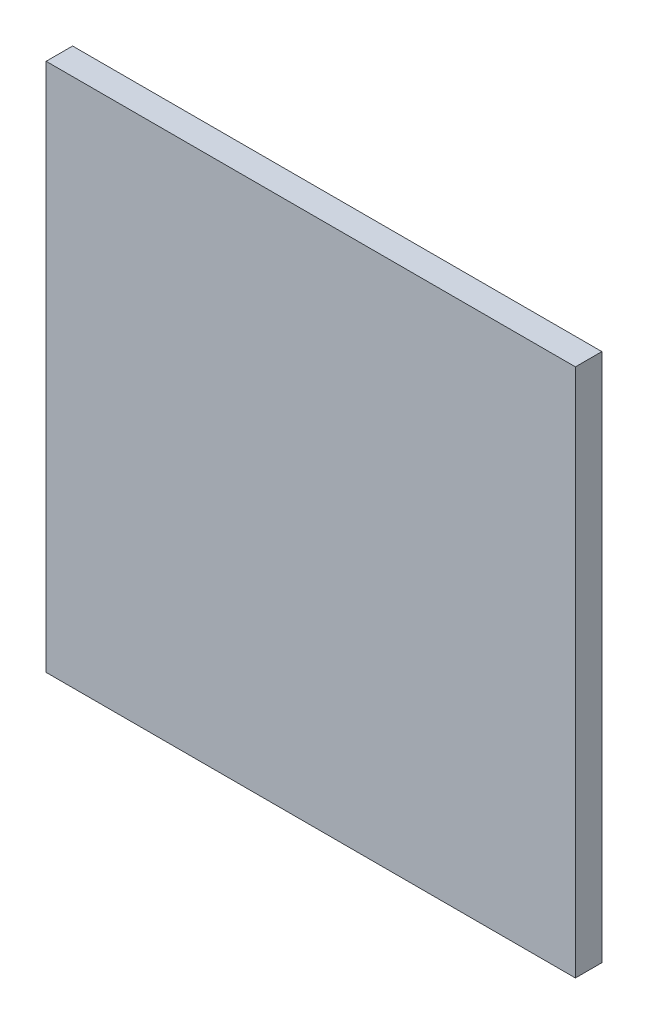
SolidWorks part; units mm, degrees
ref_plane "Front" through (0, 0, 0) normal (0, 0, 1) x (1, 0, 0)
ref_plane "Top" through (0, 0, 0) normal (0, 1, 0) x (1, 0, 0)
ref_plane "Right" through (0, 0, 0) normal (1, 0, 0) x (0, 0, -1)
other "Configuration Table"
sketch "Sketch1" plane through (0, 0, 0) normal (0, 0, 1) x (1, 0, 0)
  line L1 (-10, -10) -> (10, -10)
  line L2 (-10, -10) -> (-10, 10)
  line L3 (-10, 10) -> (10, 10)
  line L4 (10, -10) -> (10, 10)
  point P4 (0, -10)
  point P5 (10, 0)
  dimension "D1" = 20
  dimension "D2" = 20
extrude "Extrude1" add sketch "Sketch1" against normal blind 1
